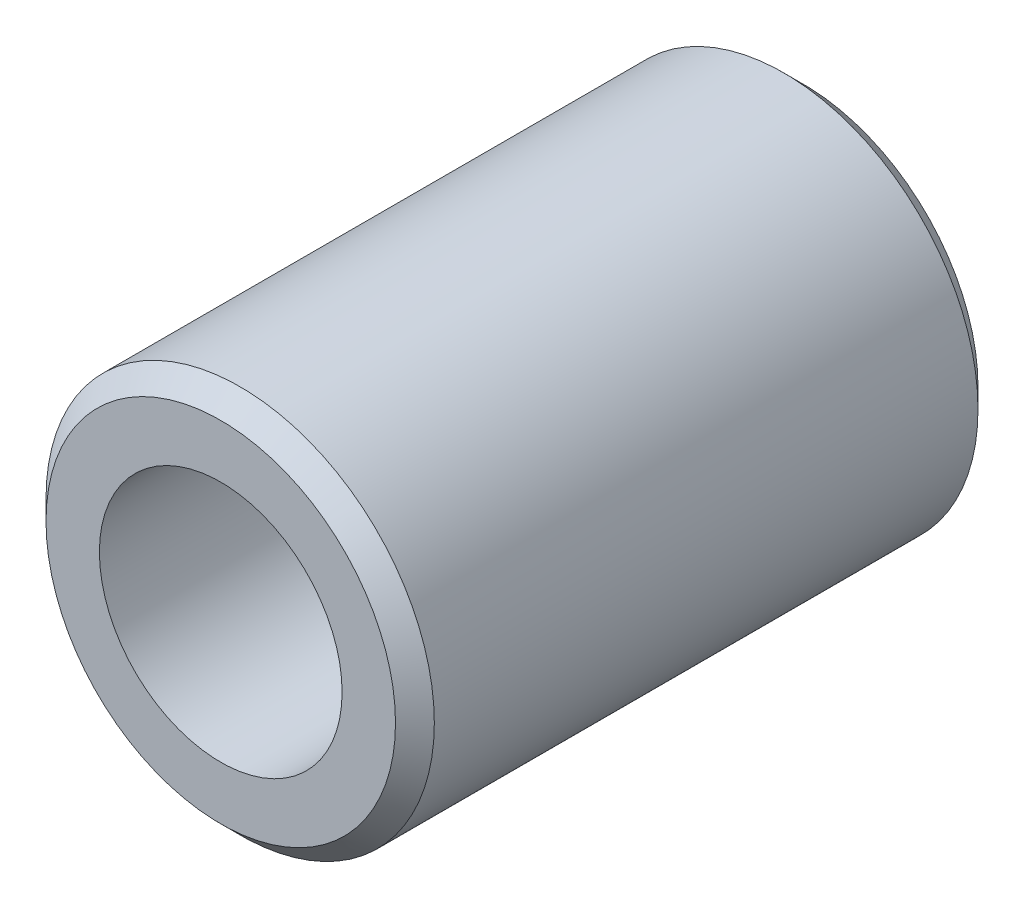
SolidWorks part; units mm, degrees
ref_plane "Front Plane" through (0, 0, 0) normal (0, 0, 1) x (1, 0, 0)
ref_plane "Top Plane" through (0, 0, 0) normal (0, 1, 0) x (1, 0, 0)
ref_plane "Right Plane" through (0, 0, 0) normal (1, 0, 0) x (0, 0, -1)
sketch "Sketch1" plane through (0, 0, 0) normal (0, 0, 1) x (1, 0, 0)
  circle A0 centre (0, 0) radius 20
  circle A1 centre (0, 0) radius 12.5
  dimension "D1" = 40
  dimension "D2" = 25
extrude "Boss-Extrude1" add sketch "Sketch1" along normal blind 60
chamfer "Chamfer1" distance 2 angle 45 2 edges at (20, 0, 60) (20, 0, 0)
